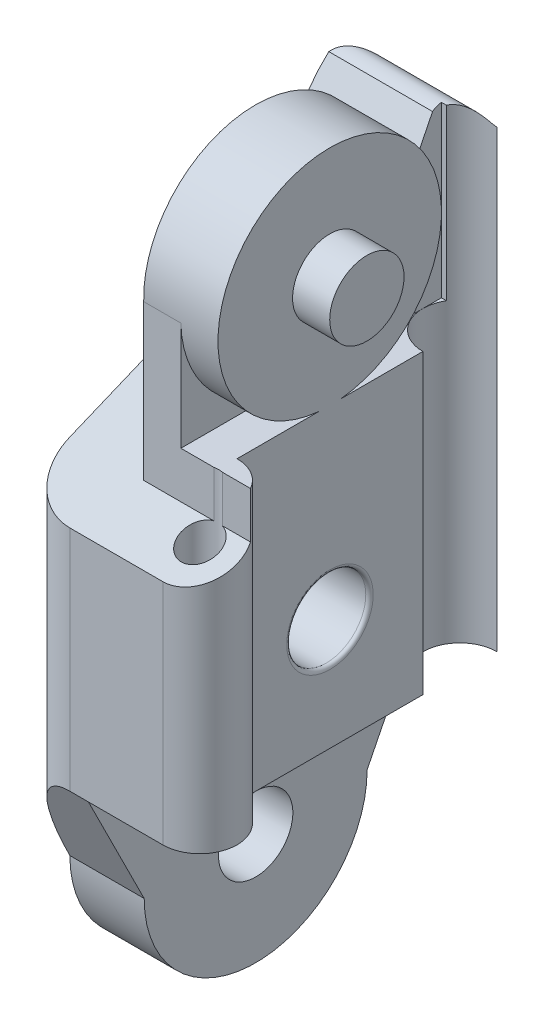
SolidWorks part; units mm, degrees
ref_plane "Front Plane" through (0, 0, 0) normal (0, 0, 1) x (1, 0, 0)
ref_plane "Top Plane" through (0, 0, 0) normal (0, 1, 0) x (1, 0, 0)
ref_plane "Right Plane" through (0, 0, 0) normal (1, 0, 0) x (0, 0, -1)
sketch "Sketch1" plane through (0, 0, 0) normal (0, 1, 0) x (1, 0, 0)
  line L0 (-20.32, 27.0953) -> (-20.32, 11.8553)
  line L1 (0, 27.0953) -> (0, 11.8553)
  line L2 (-16.51, 8.0453) -> (-3.81, 8.0453)
  line L3 (-16.51, 30.9053) -> (-3.81, 30.9053)
  arc A0 (-20.32, 11.8553) -> (-16.51, 8.0453) centre (-16.51, 11.8553) ccw
  arc A1 (-3.81, 8.0453) -> (0, 11.8553) centre (-3.81, 11.8553) ccw
  arc A2 (-20.32, 27.0953) -> (-16.51, 30.9053) centre (-16.51, 27.0953) cw
  arc A3 (0, 27.0953) -> (-3.81, 30.9053) centre (-3.81, 27.0953) ccw
  dimension "D1" = 15.24
  dimension "D2" = 20.32
  dimension "D3" = 22.86
extrude "Boss-Extrude1" add sketch "Sketch1" along normal blind 50.8
sketch "Sketch3" plane through (0, 50.8, 0) normal (0, 1, 0) x (1, 0, 0)
  line L0 (-10.16, 10.5853) -> (-10.16, 28.3653) construction
  line L1 (-16.51, 8.0453) -> (-3.81, 8.0453) construction
  line L2 (-3.81, 30.9053) -> (-16.51, 30.9053) construction
  line L3 (0, 11.8553) -> (0, 27.0953) construction
  circle A0 centre (-10.16, 10.5853) radius 1.27
  circle A1 centre (-10.16, 28.3653) radius 1.27
  dimension "D2" = 2.54
  dimension "D1" = 17.78
  dimension "D3" = 10.16
  dimension "D4" = 2.54
extrude "Cut-Extrude2" cut sketch "Sketch3" against normal blind 50.8
sketch "Sketch2" plane through (-20.32, 0, 0) normal (-1, 0, 0) x (0, 0, 1)
  line L0 (-27.0953, 7.62) -> (-30.9053, 15.24)
  line L1 (-27.0953, 50.8) -> (-27.0953, 0) construction
  line L2 (-30.9053, 15.24) -> (-30.9053, -5.08)
  line L4 (-8.0453, -5.08) -> (-8.0453, 15.24)
  line L5 (-8.0453, 15.24) -> (-11.8553, 7.62)
  line L6 (-11.8553, 50.8) -> (-11.8553, 0) construction
  line L8 (-27.0953, 0) -> (-11.8553, 0) construction
  line L9 (-30.9053, -5.08) -> (-8.0453, -5.08)
  line L10 (-30.9053, 50.8) -> (-30.9053, 0) construction
  line L11 (-8.0453, 50.8) -> (-8.0453, 0) construction
  line L12 (-11.8216, 42.9704) -> (-8.0453, 35.56)
  line L13 (-8.0453, 35.56) -> (-8.0453, 55.88)
  line L14 (-30.9053, 55.88) -> (-30.9053, 35.56)
  line L15 (-30.9053, 35.56) -> (-27.0924, 42.9516)
  line L16 (-8.0453, 55.88) -> (-30.9053, 55.88)
  line L17 (-27.0953, 50.8) -> (-11.8553, 50.8) construction
  arc A0 (-11.8553, 7.62) -> (-27.0953, 7.62) centre (-19.4753, 7.62) cw
  arc A1 (-27.0924, 42.9516) -> (-11.8216, 42.9704) centre (-19.4572, 43.1619) cw
  dimension "D1" = 20.32
  dimension "D2" = 5.08
  dimension "D3" = 20.32
  dimension "D4" = 5.08
extrude "Cut-Extrude1" cut sketch "Sketch2" against normal blind 50.8
sketch "Sketch7" plane through (0, 0, -8.0453) normal (0, 0, 1) x (1, 0, 0)
  line L0 (-15.24, 50.8) -> (-12.7, 50.8)
  line L1 (-12.7, 50.8) -> (-12.7, 35.56)
  line L4 (-7.62, 50.8) -> (-5.08, 50.8)
  line L8 (0, 59.1564) -> (-20.32, 59.1564)
  line L12 (0, 43.9043) -> (0, 7.62) construction
  line L13 (-20.32, 43.9043) -> (-20.32, 7.62) construction
  line L16 (-7.62, 50.8) -> (-7.62, 35.56)
  line L17 (-7.62, 35.56) -> (-12.7, 35.56)
  line L18 (-20.32, 35.56) -> (-15.24, 35.56)
  line L19 (-15.24, 35.56) -> (-15.24, 50.8)
  line L20 (-5.08, 50.8) -> (-5.08, 35.56)
  line L21 (-5.08, 35.56) -> (0, 35.56)
  line L22 (-20.32, 35.56) -> (-20.32, 59.1564)
  line L23 (0, 59.1564) -> (0, 35.56)
  dimension "D3" = 15.24
extrude "Cut-Extrude6" cut sketch "Sketch7" against normal blind 50.8
sketch "Sketch9" plane through (-20.32, 0, 0) normal (-1, 0, 0) x (0, 0, 1)
  line L0 (-19.4753, 35.56) -> (-30.9611, 35.56)
  line L1 (-27.0953, 35.56) -> (-11.8553, 35.56) construction
  line L2 (-30.9611, 35.56) -> (-30.9611, 50.8) construction
  line L4 (-27.0928, 42.9858) -> (-30.9611, 50.8) construction
  line L5 (-30.9611, 35.56) -> (-30.9611, 45.9354)
  line L6 (-27.0928, 42.9858) -> (-29.027, 46.8929)
  arc A0 (-19.4753, 35.56) -> (-27.0928, 42.9858) centre (-19.4753, 43.18) cw
  arc A1 (-30.9611, 45.9354) -> (-29.027, 46.8929) centre (-29.7571, 45.9354) cw
  dimension "D1" = 7.62
  dimension "D2" = 15.24
extrude "Boss-Extrude3" add sketch "Sketch9" against normal blind 20.32
sketch "Sketch4" plane through (0, 0, -8.0453) normal (0, 0, 1) x (1, 0, 0)
  line L0 (-15.24, 15.24) -> (-15.24, 0)
  line L1 (-15.24, 0) -> (-5.08, 0)
  line L2 (-5.08, 0) -> (-5.08, 15.24)
  line L3 (-5.08, 15.24) -> (-15.24, 15.24)
  line L4 (0, 0) -> (0, 7.62) construction
  dimension "D1" = 10.16
  dimension "D2" = 5.08
  dimension "D3" = 15.24
extrude "Cut-Extrude3" cut sketch "Sketch4" against normal blind 50.8
sketch "Sketch5" plane through (-20.32, 0, 0) normal (-1, 0, 0) x (0, 0, 1)
  line L0 (-27.0953, 35.56) -> (-27.0953, 7.62) construction
  circle A0 centre (-19.4753, 7.62) radius 2.54
  arc A1 (-27.0953, 7.62) -> (-11.8553, 7.62) centre (-19.4753, 7.62) ccw construction
  point P5 (-19.4753, 0)
  dimension "D3" = 5.08
  dimension "D1" = 7.62
  dimension "D2" = 7.62
extrude "Cut-Extrude5" cut sketch "Sketch5" against normal blind 50.8
sketch "Sketch8" plane through (-15.24, 0, 0) normal (-1, 0, 0) x (0, 0, 1)
  circle A0 centre (-19.4416, 43.18) radius 2.54
  arc A1 (-11.8216, 42.9704) -> (-27.0933, 42.9867) centre (-19.4572, 43.1619) ccw construction
  point P6 (-19.4491, 50.8)
  dimension "D1" = 5.08
  dimension "D2" = 7.62
  dimension "D3" = 7.62
extrude "Boss-Extrude2" add sketch "Sketch8" along normal blind 2.54
pattern_linear "LPattern1" count 2 spacing 12.7 along (1, 0, 0) of "Boss-Extrude2"
sketch "Sketch10" plane through (0, 35.56, 0) normal (0, -1, 0) x (1, 0, 0)
  line L0 (-16.51, -30.9053) -> (-3.81, -30.9053)
  line L1 (0, -27.0953) -> (5.7709, -37.2588)
  line L2 (5.7709, -37.2588) -> (-26.7978, -37.8907)
  line L3 (-26.7978, -37.8907) -> (-20.32, -27.0953)
  arc A0 (-3.81, -30.9053) -> (0, -27.0953) centre (-3.81, -27.0953) ccw
  arc A1 (-16.51, -30.9053) -> (-20.32, -27.0953) centre (-16.51, -27.0953) cw
extrude "Cut-Extrude7" cut sketch "Sketch10" against normal blind 20.32
sketch "Sketch12" plane through (0, 0, -8.0453) normal (0, 0, 1) x (1, 0, 0)
  line L0 (-12.7, 35.56) -> (-7.62, 35.56)
  line L1 (-12.7, 35.56) -> (-12.7, 55.5014)
  line L2 (-7.62, 35.56) -> (-7.62, 55.5014)
  line L3 (-12.7, 55.5014) -> (-7.62, 55.5014)
extrude "Cut-Extrude8" cut sketch "Sketch12" against normal blind 21.59
sketch "Sketch13" plane through (-20.32, 0, 0) normal (-1, 0, 0) x (0, 0, 1)
  line L0 (-19.4753, 35.56) -> (-8.0453, 30.8255)
  line L1 (-19.4753, 35.56) -> (-11.8553, 35.56) construction
  line L2 (-19.4753, 35.56) -> (-1.3207, 35.56)
  line L3 (-1.3207, 35.56) -> (-1.3207, 30.8255)
  line L4 (-1.3207, 30.8255) -> (-8.0453, 30.8255)
  line L5 (-8.0453, 35.56) -> (-8.0453, 15.24) construction
extrude "Cut-Extrude9" cut sketch "Sketch13" against normal blind 5.08
pattern_linear "LPattern2" count 2 spacing 15.24 along (1, 0, 0) of "Cut-Extrude9"
sketch "Sketch15" plane through (0, 35.56, 0) normal (0, 1, 0) x (1, 0, 0)
  line L0 (-10.16, 25.8253) -> (-10.16, 13.1253)
  line L1 (-12.7, 8.0453) -> (-7.62, 8.0453) construction
  line L2 (-10.16, 30.9053) -> (8.972, 40.3855)
  line L3 (8.972, 40.3855) -> (12.1247, -15.9891)
  line L4 (12.1247, -15.9891) -> (-10.16, 8.0453)
  line L5 (-5.08, 30.9053) -> (-15.24, 30.9053) construction
  arc A0 (-10.16, 25.8253) -> (-10.16, 30.9053) centre (-10.16, 28.3653) cw
  arc A1 (-10.16, 13.1253) -> (-10.16, 8.0453) centre (-10.16, 10.5853) cw
  circle A2 centre (-10.16, 28.3653) radius 1.27 construction
  circle A3 centre (-10.16, 10.5853) radius 1.27 construction
extrude "Cut-Extrude10" cut sketch "Sketch15" against normal mid plane 81.534
sketch "Sketch14" plane through (-12.7, 0, 0) normal (1, 0, 0) x (0, 0, -1)
  circle A0 centre (19.4572, 43.1619) radius 7.6381
extrude "Boss-Extrude4" add sketch "Sketch14" along normal blind 2.54
sketch "Sketch16" plane through (-10.16, 0, 0) normal (1, 0, 0) x (0, 0, -1)
  circle A0 centre (19.4572, 43.1619) radius 2.54
  dimension "D1" = 5.08
extrude "Boss-Extrude5" add sketch "Sketch16" along normal blind 2.54
sketch "Sketch18" plane through (-10.16, 0, 0) normal (1, 0, 0) x (0, 0, -1)
  line L0 (25.8253, 15.24) -> (13.1253, 15.24) construction
  line L1 (15.6653, 17.78) -> (23.2853, 17.78)
  line L2 (15.6653, 17.78) -> (15.6653, 33.02)
  line L3 (15.6653, 33.02) -> (23.2853, 33.02)
  line L4 (23.2853, 17.78) -> (23.2853, 33.02)
  line L5 (13.1253, 35.56) -> (18.7149, 35.56) construction
  line L6 (13.1253, 15.24) -> (13.1253, 35.56) construction
  line L7 (25.8253, 15.24) -> (25.8253, 35.56) construction
  dimension "D1" = 2.54
  dimension "D2" = 2.54
  dimension "D3" = 2.54
  dimension "D4" = 2.54
sketch "Sketch21" plane through (-15.24, 0, 0) normal (-1, 0, 0) x (0, 0, 1)
  line L0 (-8.0453, 35.56) -> (-11.8216, 35.56)
  line L1 (-8.0453, 35.56) -> (-8.0453, 42.9704)
  line L2 (-11.8216, 35.56) -> (-11.8216, 42.9704)
  line L3 (-8.0453, 42.9704) -> (-11.8216, 42.9704)
extrude "Cut-Extrude14" cut sketch "Sketch21" against normal blind 2.54
sketch "Sketch22" plane through (-15.24, 0, 0) normal (-1, 0, 0) x (0, 0, 1)
  line L0 (-8.0453, 30.8255) -> (-11.8216, 32.3897)
  line L1 (-19.4753, 35.56) -> (-8.0453, 30.8255) construction
  line L2 (-11.8216, 32.3897) -> (-11.8216, 35.56)
  line L3 (-11.8216, 35.56) -> (-8.0453, 35.56)
  line L4 (-8.0453, 35.56) -> (-8.0453, 30.8255)
extrude "Cut-Extrude15" cut sketch "Sketch22" against normal blind 9.906
sketch "Sketch23" plane through (-10.16, 0, 0) normal (1, 0, 0) x (0, 0, -1)
  line L0 (25.8253, 15.24) -> (13.1253, 15.24) construction
  line L1 (25.8253, 15.24) -> (25.8253, 35.56) construction
  circle A0 centre (19.4753, 22.86) radius 2.7
  dimension "D1" = 5.4
  dimension "D2" = 7.62
  dimension "D3" = 6.35
extrude "Cut-Extrude16" cut sketch "Sketch23" against normal blind 4.2
fillet "Fillet1" radius 0.254 1 edges at (-10.16, 22.86, -22.1753)
sketch "Sketch24" plane through (-14.36, 0, 0) normal (1, 0, 0) x (0, 0, -1)
  circle A0 centre (19.4753, 22.86) radius 1.7526
  dimension "D1" = 3.5052
extrude "Cut-Extrude17" cut sketch "Sketch24" against normal blind 5.47
